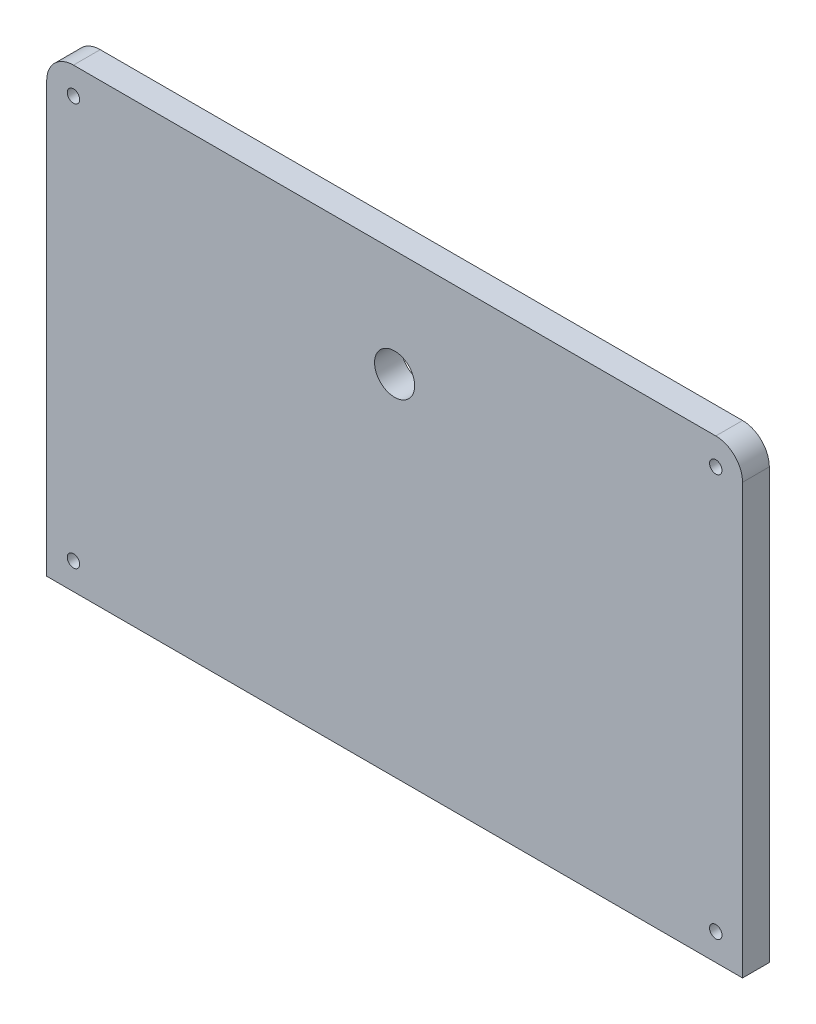
SolidWorks part; units mm, degrees
ref_plane "Front Plane" through (0, 0, 0) normal (0, 0, 1) x (1, 0, 0)
ref_plane "Top Plane" through (0, 0, 0) normal (0, 1, 0) x (1, 0, 0)
ref_plane "Right Plane" through (0, 0, 0) normal (1, 0, 0) x (0, 0, -1)
sketch "Sketch1" plane through (0, 0, 0) normal (0, 0, 1) x (1, 0, 0)
  line L0 (0, 0) -> (0, 101.854)
  line L1 (0, 0) -> (165.1, 0)
  line L2 (6.35, 108.204) -> (158.75, 108.204)
  line L3 (165.1, 0) -> (165.1, 101.854)
  arc A0 (158.75, 108.204) -> (165.1, 101.854) centre (158.75, 101.854) cw
  arc A1 (0, 101.854) -> (6.35, 108.204) centre (6.35, 101.854) cw
  circle A2 centre (6.35, 6.35) radius 1.4732
  circle A3 centre (158.75, 6.35) radius 1.4732
  circle A4 centre (158.75, 101.854) radius 1.4732
  circle A5 centre (6.35, 101.854) radius 1.4732
  circle A6 centre (82.55, 82.804) radius 4.7625
  point P9 (0, 108.204)
  dimension "D3" = 6.35
  dimension "D4" = 2.9464
  dimension "D5" = 2.9464
  dimension "D6" = 2.9464
  dimension "D7" = 2.9464
  dimension "D12" = 9.525
  dimension "D1" = 165.1
  dimension "D2" = 108.204
  dimension "D8" = 6.35
  dimension "D9" = 6.35
  dimension "D10" = 6.35
  dimension "D11" = 6.35
  dimension "D13" = 25.4
  dimension "D14" = 82.55
extrude "Boss-Extrude1" add sketch "Sketch1" along normal blind 6.35
